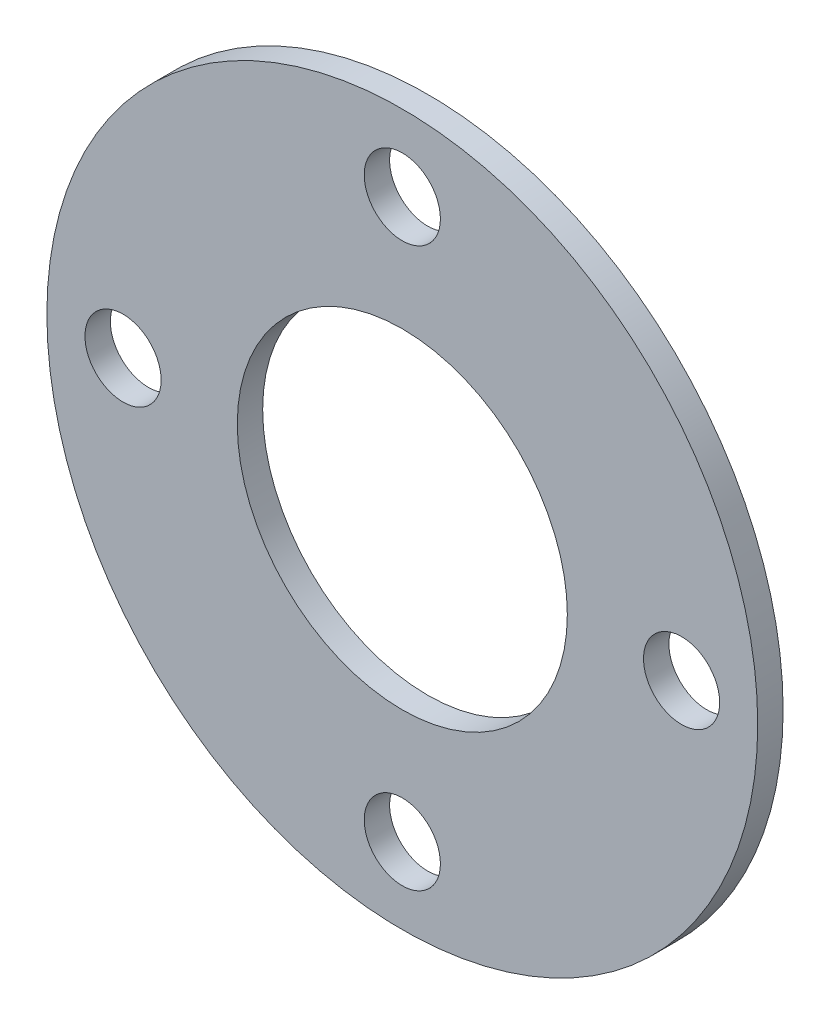
SolidWorks part; units mm, degrees
ref_plane "Front Plane" through (0, 0, 0) normal (0, 0, 1) x (1, 0, 0)
ref_plane "Top Plane" through (0, 0, 0) normal (0, 1, 0) x (1, 0, 0)
ref_plane "Right Plane" through (0, 0, 0) normal (1, 0, 0) x (0, 0, -1)
sketch "Sketch1" plane through (0, 0, 0) normal (0, 0, 1) x (1, 0, 0)
  circle A0 centre (0, 0) radius 11 construction
  circle A1 centre (11, 0) radius 1.5
  circle A2 centre (0, -11) radius 1.5
  circle A3 centre (-11, 0) radius 1.5
  circle A4 centre (0, 11) radius 1.5
  circle A5 centre (0, 0) radius 14
  circle A6 centre (0, 0) radius 6.5
  point P14 (0, 0)
  dimension "D1" = 22
  dimension "D2" = 3
  dimension "D4" = 13
  dimension "D5" = 28
  dimension "D6" = 11
  dimension "D7" = 11
  dimension "D3" = 4
extrude "Boss-Extrude1" add sketch "Sketch1" along normal blind 1 contours A0
